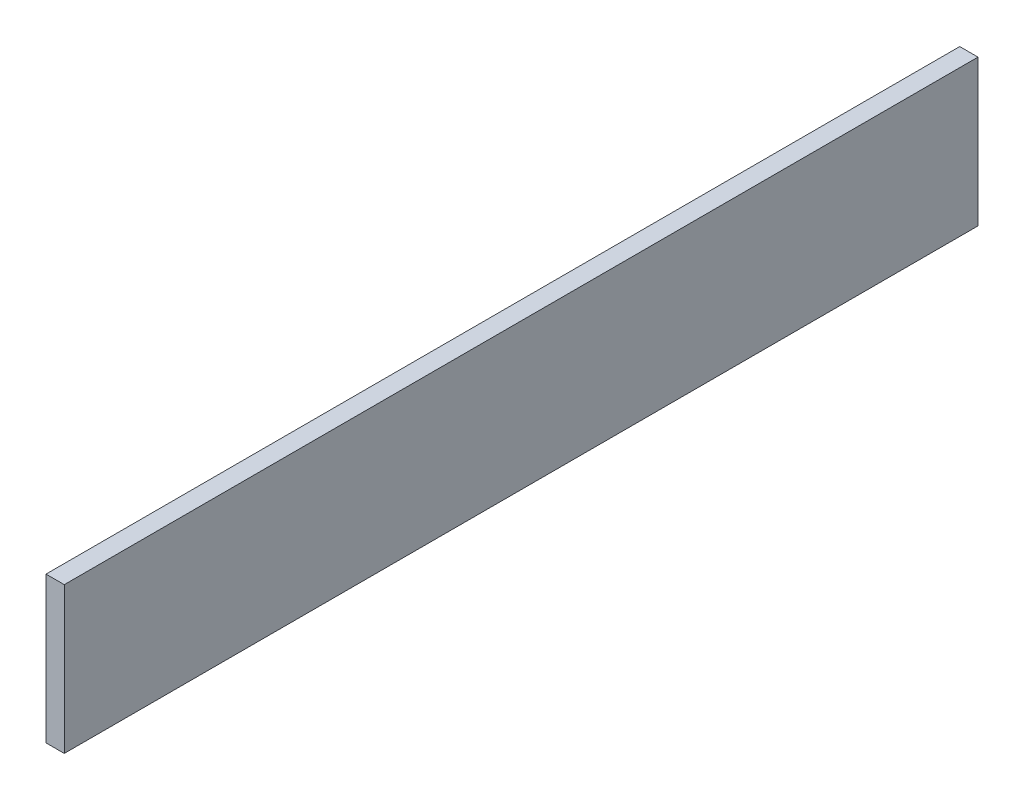
SolidWorks part; units mm, degrees
ref_plane "Ön Düzlem" through (0, 0, 0) normal (0, 0, 1) x (1, 0, 0)
ref_plane "Üst Düzlem" through (0, 0, 0) normal (0, 1, 0) x (1, 0, 0)
ref_plane "Sağ Düzlem" through (0, 0, 0) normal (1, 0, 0) x (0, 0, -1)
sketch "Sketch1" plane through (0, 0, 0) normal (0, 0, 1) x (1, 0, 0)
  line L2 (8, 10) -> (8, 90)
  line L5 (-2, 90) -> (-2, 10)
  line L6 (8, 90) -> (-2, 90)
  line L7 (8, 10) -> (-2, 10)
  dimension "D1" = 10
  dimension "D3" = 80
extrude "Boss-Extrude1" add sketch "Sketch1" along normal blind 500
